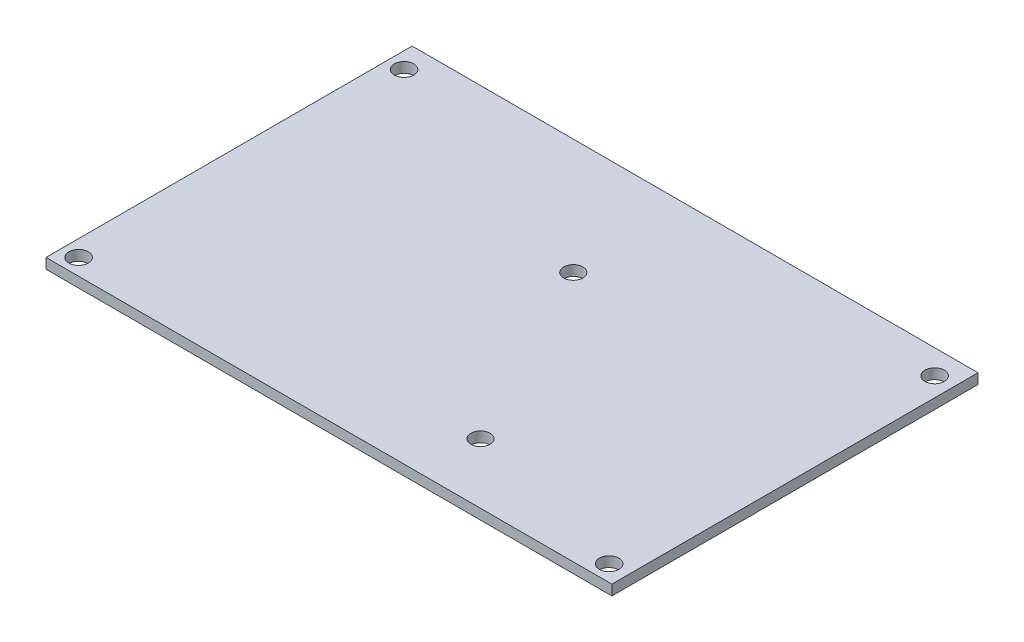
SolidWorks part; units mm, degrees
ref_plane "Přední" through (0, 0, 0) normal (0, 0, 1) x (1, 0, 0)
ref_plane "Horní" through (0, 0, 0) normal (0, 1, 0) x (1, 0, 0)
ref_plane "Pravá" through (0, 0, 0) normal (1, 0, 0) x (0, 0, -1)
sketch "Skica2" plane through (0, 0, 0) normal (0, 1, 0) x (1, 0, 0)
  line L0 (1.524, 8.636) -> (89.84, 8.636)
  line L1 (89.84, 8.636) -> (89.84, 65.776)
  line L2 (89.84, 65.776) -> (1.524, 65.776)
  line L3 (1.524, 65.776) -> (1.524, 8.636)
  circle A0 centre (4.064, 61.976) radius 1.524
  circle A1 centre (4.064, 11.176) radius 1.524
  circle A2 centre (86.868, 11.176) radius 1.524
  circle A3 centre (86.868, 61.976) radius 1.524
  circle A1829 centre (59.944, 18.034) radius 1.5
  circle A1830 centre (44.704, 47.752) radius 1.5
extrude "Přidat vysunutím1" add sketch "Skica2" along normal blind 1.6
